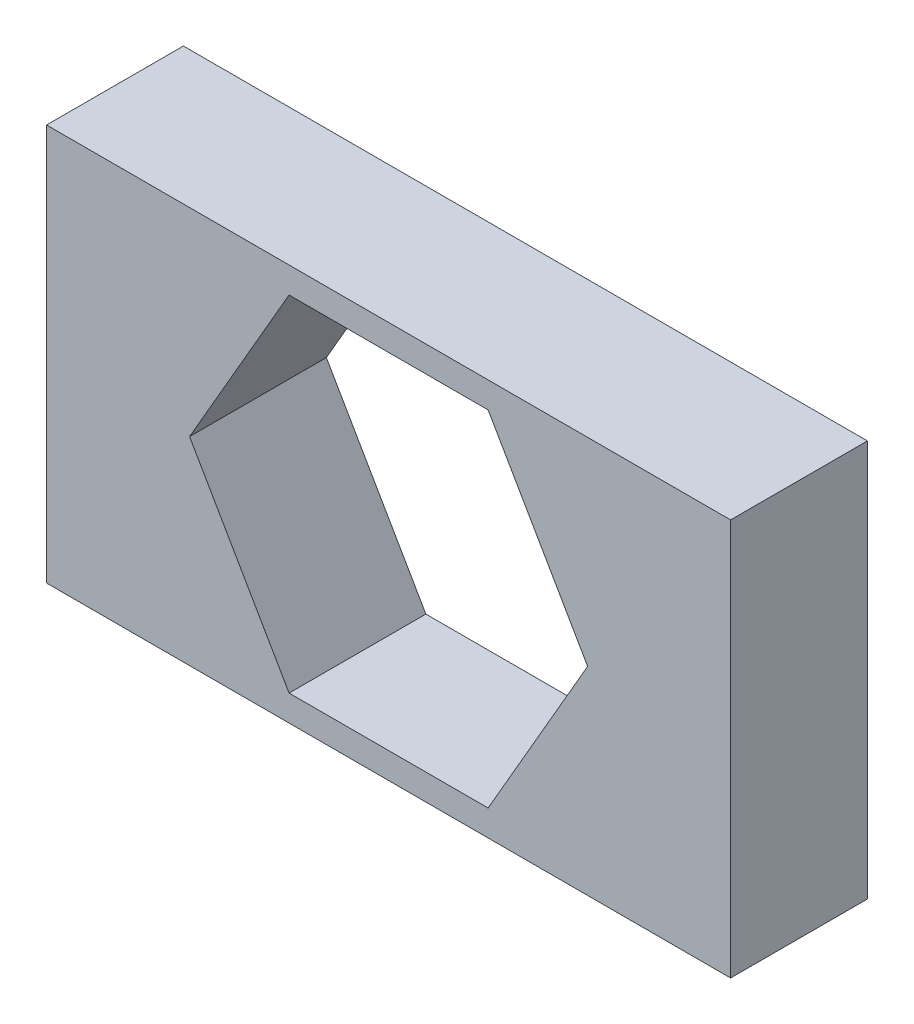
SolidWorks part; units mm, degrees
ref_plane "Plan de face" through (0, 0, 0) normal (0, 0, 1) x (1, 0, 0)
ref_plane "Plan de dessus" through (0, 0, 0) normal (0, 1, 0) x (1, 0, 0)
ref_plane "Plan de droite" through (0, 0, 0) normal (1, 0, 0) x (0, 0, -1)
sketch "Esquisse1" plane through (0, 0, 0) normal (0, 0, 1) x (1, 0, 0)
  line L0 (0, 7.25) -> (25, 7.25) construction
  line L1 (0, 0) -> (25, 0)
  line L2 (0, 0) -> (0, 14.5)
  line L3 (0, 14.5) -> (25, 14.5)
  line L4 (25, 0) -> (25, 14.5)
  line L6 (19.7746, 7.25) -> (16.1373, 13.55)
  line L7 (16.1373, 13.55) -> (8.8627, 13.55)
  line L8 (8.8627, 13.55) -> (5.2254, 7.25)
  line L9 (5.2254, 7.25) -> (8.8627, 0.95)
  line L10 (8.8627, 0.95) -> (16.1373, 0.95)
  line L11 (16.1373, 0.95) -> (19.7746, 7.25)
  circle A0 centre (12.5, 7.25) radius 6.3 construction
  dimension "D1" = 12.6
  dimension "D2" = 14.5
  dimension "D3" = 25
extrude "Boss.-Extru.1" add sketch "Esquisse1" along normal blind 5
